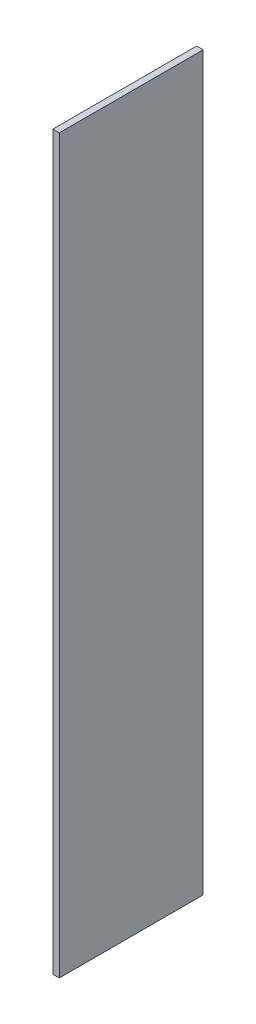
SolidWorks part; units mm, degrees
ref_plane "Front Plane" through (0, 0, 0) normal (0, 0, 1) x (1, 0, 0)
ref_plane "Top Plane" through (0, 0, 0) normal (0, 1, 0) x (1, 0, 0)
ref_plane "Right Plane" through (0, 0, 0) normal (1, 0, 0) x (0, 0, -1)
sketch "Sketch1" plane through (0, 0, 0) normal (1, 0, 0) x (0, 0, -1)
  line L1 (-28.2194, 143.51) -> (28.2194, 143.51)
  line L2 (-28.2194, 143.51) -> (-28.2194, -143.51)
  line L3 (-28.2194, -143.51) -> (28.2194, -143.51)
  line L4 (28.2194, 143.51) -> (28.2194, -143.51)
  line L5 (-28.2194, 143.51) -> (28.2194, -143.51) construction
  line L6 (-28.2194, -143.51) -> (28.2194, 143.51) construction
  point P0 (0, 0)
  dimension "D1" = 56.4388
  dimension "D2" = 287.02
extrude "Boss-Extrude1" add sketch "Sketch1" along normal blind 2.54
equation "\"motor offset\"=6mm"
equation "\"thickness0.25\"=0.225in"
equation "\"thickness0.125\"=0.122in"
equation "\"thickness_acrylic0.1\"= 0.1in"
equation "\"D1@Sketch1\"=\"thickness_acrylic0.1\"+\"thickness0.125\"+2"
